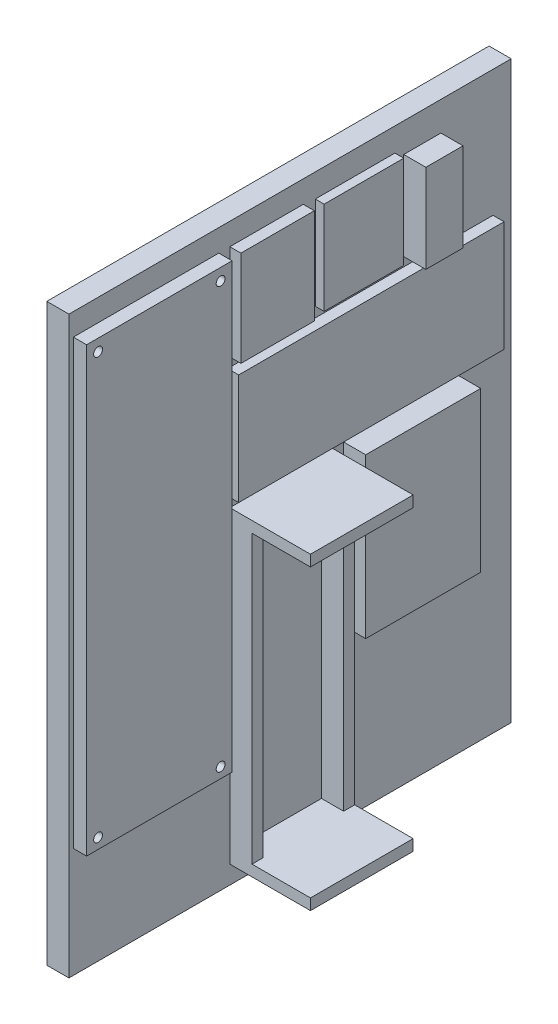
SolidWorks part; units mm, degrees
material "1060 Alloy"
ref_plane "Front Plane" through (0, 0, 0) normal (0, 0, 1) x (1, 0, 0)
ref_plane "Top Plane" through (0, 0, 0) normal (0, 1, 0) x (1, 0, 0)
ref_plane "Right Plane" through (0, 0, 0) normal (1, 0, 0) x (0, 0, -1)
sketch "Sketch1" plane through (0, 0, 0) normal (1, 0, 0) x (0, 0, -1)
  line L1 (-16.445, 50.065) -> (16.445, 50.065)
  line L2 (-16.445, 50.065) -> (-16.445, -50.065)
  line L3 (-16.445, -50.065) -> (16.445, -50.065)
  line L4 (16.445, 50.065) -> (16.445, -50.065)
  line L5 (-17.445, 55.065) -> (82.555, 55.065)
  line L6 (-17.445, 55.065) -> (-17.445, -74.935)
  line L7 (-17.445, -74.935) -> (82.555, -74.935)
  line L8 (82.555, 55.065) -> (82.555, -74.935)
  circle A0 centre (-13.855, 47.395) radius 1
  circle A4 centre (13.855, 47.395) radius 1
  circle A5 centre (13.855, -47.705) radius 1
  circle A6 centre (-13.855, -47.705) radius 1
  dimension "D3" = 2
  dimension "D4" = 2.67
  dimension "D8" = 2
  dimension "D11" = 2
  dimension "D12" = 2
  dimension "D15" = 2.36
  dimension "D1" = 32.89
  dimension "D2" = 100.13
  dimension "D5" = 2.59
  dimension "D6" = 50.065
  dimension "D7" = 16.445
  dimension "D9" = 2.59
  dimension "D10" = 2.67
  dimension "D13" = 2.59
  dimension "D14" = 2.36
  dimension "D16" = 2.59
  dimension "D17" = 95.1
  dimension "D18" = 130
  dimension "D19" = 100
  dimension "D20" = 5
  dimension "D21" = 1
extrude "Boss-Extrude1" add sketch "Sketch1" along normal blind 5 contours L4 L1 L2 L3 A6 A5 A4 A0 | L8 L5 L6 L7 L1 L4 L3 L2
sketch "Sketch3" plane through (5, 0, 0) normal (1, 0, 0) x (0, 0, -1)
  line L1 (-16.445, 50.065) -> (16.445, 50.065)
  line L2 (-16.445, 50.065) -> (-16.445, -50.065)
  line L3 (-16.445, -50.065) -> (16.445, -50.065)
  line L4 (16.445, 50.065) -> (16.445, -50.065)
  circle A0 centre (-13.855, 47.395) radius 1 construction
  circle A1 centre (13.855, 47.395) radius 1 construction
  circle A2 centre (13.855, -47.705) radius 1 construction
  circle A3 centre (-13.855, 47.395) radius 1
  circle A4 centre (13.855, 47.395) radius 1
  circle A5 centre (13.855, -47.705) radius 1
  circle A6 centre (-13.855, -47.705) radius 1
  dimension "D5" = 2
  dimension "D6" = 2.36
  dimension "D1" = 2.59
  dimension "D2" = 2.59
  dimension "D3" = 2.67
  dimension "D4" = 2.36
  dimension "D7" = 2.59
extrude "Boss-Extrude3" add sketch "Sketch3" along normal blind 3
sketch "Sketch4" plane through (5, 0, 0) normal (1, 0, 0) x (0, 0, -1)
  line L1 (18.945, 50.065) -> (35.545, 50.065)
  line L2 (18.945, 50.065) -> (18.945, 28.465)
  line L3 (18.945, 28.465) -> (35.545, 28.465)
  line L4 (35.545, 50.065) -> (35.545, 28.465)
  line L10 (16.445, -50.065) -> (16.445, 50.065) construction
  line L11 (16.445, 50.065) -> (-16.445, 50.065) construction
  point P4 (35.545, 39.265)
  point P7 (0, 50.065)
  dimension "D1" = 16.6
  dimension "D2" = 21.6
  dimension "D3" = 0
  dimension "D6" = 2.5
extrude "Boss-Extrude4" add sketch "Sketch4" along normal blind 2.5
sketch "Sketch5" plane through (5, 0, 0) normal (1, 0, 0) x (0, 0, -1)
  line L1 (18.445, 26.465) -> (78.445, 26.465)
  line L2 (18.445, 26.465) -> (18.445, 1.465)
  line L3 (18.445, 1.465) -> (78.445, 1.465)
  line L4 (78.445, 26.465) -> (78.445, 1.465)
  line L5 (18.945, 28.465) -> (35.545, 28.465) construction
  line L6 (16.445, -50.065) -> (16.445, 50.065) construction
  dimension "D1" = 60
  dimension "D2" = 25
  dimension "D3" = 2
  dimension "D4" = 2
extrude "Boss-Extrude5" add sketch "Sketch5" along normal blind 2.5
sketch "Sketch6" plane through (5, 0, 0) normal (1, 0, 0) x (0, 0, -1)
  line L1 (38.2605, 49.7462) -> (56.2605, 49.7462)
  line L2 (38.2605, 49.7462) -> (38.2605, 28.7462)
  line L3 (38.2605, 28.7462) -> (56.2605, 28.7462)
  line L4 (56.2605, 49.7462) -> (56.2605, 28.7462)
  dimension "D1" = 18
  dimension "D2" = 21
extrude "Boss-Extrude6" add sketch "Sketch6" along normal blind 2
sketch "Sketch7" plane through (5, 0, 0) normal (1, 0, 0) x (0, 0, -1)
  line L0 (56.2605, 28.7462) -> (56.2605, 49.7462) construction
  line L1 (58.2605, 48.465) -> (66.6605, 48.465)
  line L2 (58.2605, 48.465) -> (58.2605, 28.465)
  line L3 (58.2605, 28.465) -> (66.6605, 28.465)
  line L4 (66.6605, 48.465) -> (66.6605, 28.465)
  line L5 (78.445, 26.465) -> (18.445, 26.465) construction
  dimension "D1" = 8.4
  dimension "D2" = 20
  dimension "D3" = 2
  dimension "D4" = 2
extrude "Boss-Extrude7" add sketch "Sketch7" along normal blind 5
sketch "Sketch9" plane through (5, 0, 0) normal (1, 0, 0) x (0, 0, -1)
  line L0 (18.445, 1.465) -> (78.445, 1.465) construction
  line L1 (21.445, -3.535) -> (39.665, -3.535)
  line L2 (21.445, -3.535) -> (21.445, -68.335)
  line L3 (21.445, -68.335) -> (39.665, -68.335)
  line L4 (39.665, -3.535) -> (39.665, -68.335)
  line L5 (16.445, -50.065) -> (16.445, 50.065) construction
  line L7 (21.445, -3.535) -> (18.945, -3.535)
  line L8 (21.445, -3.535) -> (21.445, -68.335)
  line L9 (21.445, -68.335) -> (18.945, -68.335)
  line L10 (18.945, -3.535) -> (18.945, -68.335)
  line L11 (39.665, -3.535) -> (42.165, -3.535)
  line L12 (39.665, -3.535) -> (39.665, -68.335)
  line L13 (39.665, -68.335) -> (42.165, -68.335)
  line L14 (42.165, -3.535) -> (42.165, -68.335)
  line L15 (18.945, -68.335) -> (42.165, -68.335)
  line L19 (42.165, -3.535) -> (18.945, -3.535)
  dimension "D1" = 18.22
  dimension "D2" = 64.8
  dimension "D3" = 5
  dimension "D4" = 5
  dimension "D5" = 2.5
  dimension "D6" = 2.5
extrude "Boss-Extrude8" add sketch "Sketch9" along normal blind 5 contours L7 L10 L9 L2 | L14 L11 L4 L13
sketch "Sketch10" plane through (5, 0, 0) normal (1, 0, 0) x (0, 0, -1)
  line L1 (18.945, -68.335) -> (42.165, -68.335)
  line L2 (18.945, -68.335) -> (18.945, -70.835)
  line L3 (18.945, -70.835) -> (42.165, -70.835)
  line L4 (42.165, -68.335) -> (42.165, -70.835)
  line L5 (18.945, -3.535) -> (42.165, -3.535)
  line L6 (18.945, -3.535) -> (18.945, -1.035)
  line L7 (18.945, -1.035) -> (42.165, -1.035)
  line L8 (42.165, -3.535) -> (42.165, -1.035)
  dimension "D1" = 2.5
  dimension "D2" = 2.5
extrude "Boss-Extrude9" add sketch "Sketch10" along normal blind 18.22
sketch "Sketch11" plane through (5, 0, 0) normal (1, 0, 0) x (0, 0, -1)
  line L0 (42.165, -3.535) -> (42.165, -68.335) construction
  line L1 (44.665, -1.035) -> (70.665, -1.035)
  line L2 (44.665, -1.035) -> (44.665, -37.035)
  line L3 (44.665, -37.035) -> (70.665, -37.035)
  line L4 (70.665, -1.035) -> (70.665, -37.035)
  line L5 (18.445, 1.465) -> (78.445, 1.465) construction
  dimension "D1" = 2.5
  dimension "D2" = 2.5
  dimension "D3" = 36
  dimension "D4" = 26
sketch "Sketch12" plane through (5, 0, 0) normal (1, 0, 0) x (0, 0, -1)
  line L0 (42.165, -3.535) -> (42.165, -68.335) construction
  line L1 (44.665, -1.035) -> (70.665, -1.035)
  line L2 (44.665, -1.035) -> (44.665, -37.035)
  line L3 (44.665, -37.035) -> (70.665, -37.035)
  line L4 (70.665, -1.035) -> (70.665, -37.035)
  line L5 (18.445, 1.465) -> (78.445, 1.465) construction
  dimension "D1" = 2.5
  dimension "2.5" = 2.5
  dimension "D2" = 36
  dimension "D3" = 26
extrude "Boss-Extrude11" add sketch "Sketch12" along normal blind 5 contours L2 L1 L4 L3
extrude "Boss-Extrude10" add sketch "Sketch11" along normal blind 5
